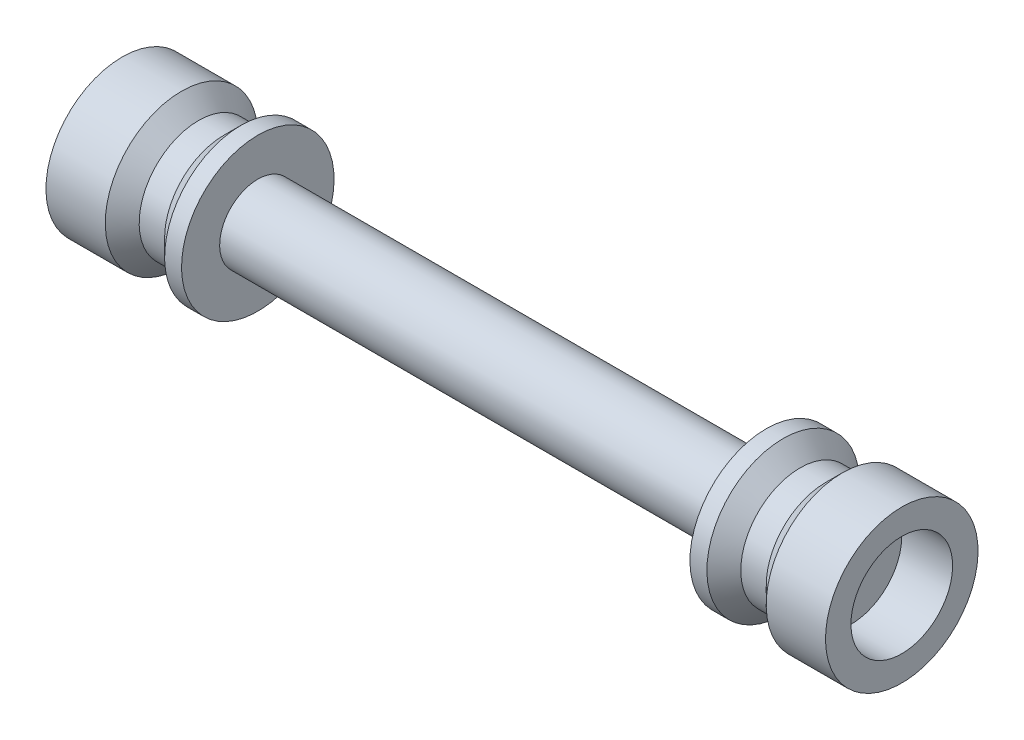
SolidWorks part; units mm, degrees
ref_plane "Front" through (0, 0, 0) normal (0, 0, 1) x (1, 0, 0)
ref_plane "Top" through (0, 0, 0) normal (0, 1, 0) x (1, 0, 0)
ref_plane "Right" through (0, 0, 0) normal (1, 0, 0) x (0, 0, -1)
sketch "Esquisse1" plane through (0, 0, 0) normal (0, 0, 1) x (1, 0, 0)
  line L0 (0, 0) -> (0, 11.3185) construction
  line L1 (0, 0) -> (-20, 0)
  line L2 (-20, 0) -> (-20, 3)
  line L3 (-20, 3) -> (-23, 3)
  line L4 (-23, 3) -> (-23, 4.5)
  line L5 (-23, 4.5) -> (-19.5, 4.5)
  line L6 (-19.5, 4.5) -> (-18.5, 3.5)
  line L7 (-18.5, 3.5) -> (-17, 3.5)
  line L8 (-17, 3.5) -> (-16, 4.5)
  line L9 (-16, 4.5) -> (-15, 4.5)
  line L10 (-15, 4.5) -> (-15, 2.25)
  line L11 (-15, 2.25) -> (15, 2.25)
  line L12 (15, 4.5) -> (15, 2.25)
  line L13 (16, 4.5) -> (15, 4.5)
  line L14 (17, 3.5) -> (16, 4.5)
  line L15 (18.5, 3.5) -> (17, 3.5)
  line L16 (19.5, 4.5) -> (18.5, 3.5)
  line L17 (23, 4.5) -> (19.5, 4.5)
  line L18 (23, 3) -> (23, 4.5)
  line L19 (20, 3) -> (23, 3)
  line L20 (20, 0) -> (20, 3)
  line L21 (0, 0) -> (20, 0)
  line L22 (0, 0) -> (-29.7186, 0) construction
  point P15 (0, 2.25)
  dimension "D1" = 30
  dimension "D2" = 4.5
  dimension "D3" = 9
  dimension "D4" = 7
  dimension "D5" = 45
  dimension "D6" = 8
  dimension "D7" = 1
  dimension "D8" = 1.5
  dimension "D9" = 1.5
  dimension "D10" = 3
revolve "Revolution1" add sketch "Esquisse1" angle 360 about L22
chamfer "Chamfer1" [suppressed] distance 0.5 angle 45
